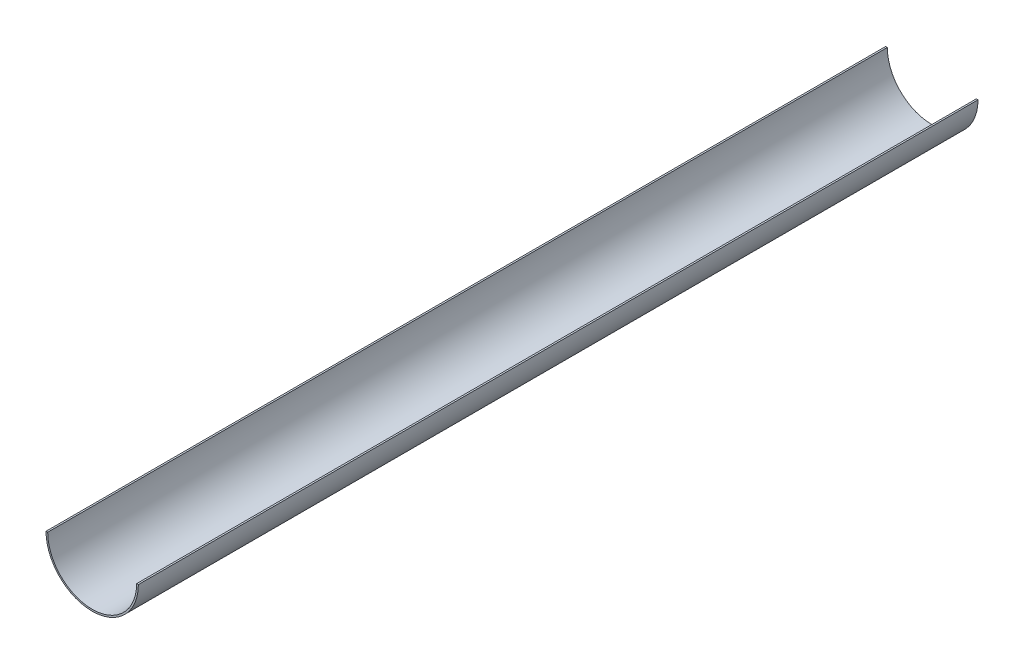
SolidWorks part; units mm, degrees
ref_plane "Front Plane" through (0, 0, 0) normal (0, 0, 1) x (1, 0, 0)
ref_plane "Top Plane" through (0, 0, 0) normal (0, 1, 0) x (1, 0, 0)
ref_plane "Right Plane" through (0, 0, 0) normal (1, 0, 0) x (0, 0, -1)
sketch "Sketch1" plane through (0, 0, 0) normal (0, 0, 1) x (1, 0, 0)
  line L0 (-53, 0) -> (-55, 0)
  line L1 (53, 0) -> (55, 0)
  arc A0 (-55, 0) -> (55, 0) centre (0, 0) ccw
  arc A1 (-53, 0) -> (53, 0) centre (0, 0) ccw
  dimension "D1" = 110
  dimension "D2" = 106
extrude "Boss-Extrude1" add sketch "Sketch1" along normal blind 1000
